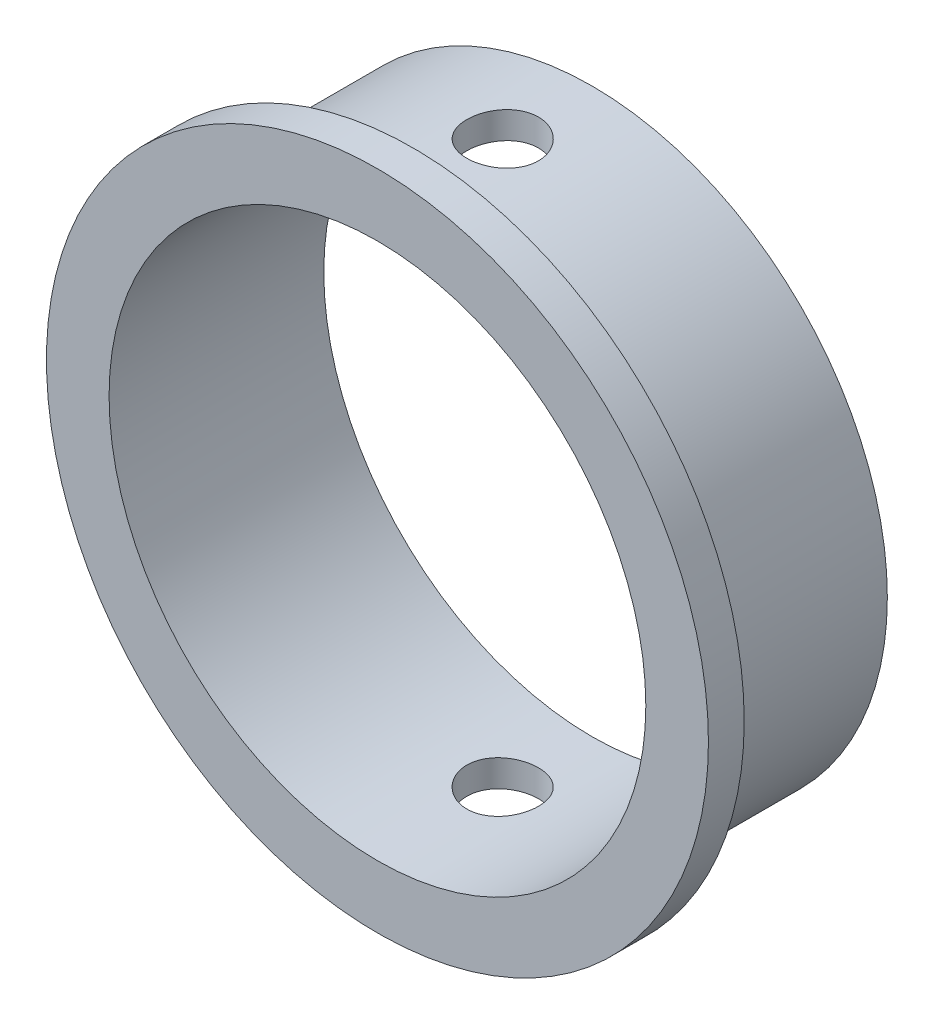
SolidWorks part; units mm, degrees
ref_plane "Alzado" through (0, 0, 0) normal (0, 0, 1) x (1, 0, 0)
ref_plane "Planta" through (0, 0, 0) normal (0, 1, 0) x (1, 0, 0)
ref_plane "Vista lateral" through (0, 0, 0) normal (1, 0, 0) x (0, 0, -1)
sketch "Croquis2" plane through (0, 0, 0) normal (0, 0, 1) x (1, 0, 0)
  circle A0 centre (0, 0) radius 16.5
  circle A1 centre (0, 0) radius 15
  dimension "D1" = 33
  dimension "D2" = 30
extrude "Saliente-Extruir1" add sketch "Croquis2" along normal blind 12
sketch "Croquis3" plane through (0, 0, 12) normal (0, 0, 1) x (1, 0, 0)
  circle A0 centre (0, 0) radius 15
  circle A1 centre (0, 0) radius 18.5
  circle A2 centre (0, 0) radius 16.5 construction
  dimension "D1" = 2
extrude "Saliente-Extruir2" add sketch "Croquis3" against normal blind 2 contours A1
sketch "Croquis4" plane through (0, 0, 10) normal (0, 0, -1) x (-1, 0, 0)
  circle A0 centre (0, 0) radius 15
extrude "Cortar-Extruir1" cut sketch "Croquis4" against normal blind 2
sketch "Croquis5" plane through (0, 0, 0) normal (0, 1, 0) x (1, 0, 0)
  line L0 (-16.5, -5) -> (16.5, -5) construction
  line L1 (-16.5, 0) -> (-16.5, -10) construction
  line L2 (16.5, -10) -> (16.5, 0) construction
  line L3 (0, 0) -> (0, -10) construction
  line L4 (18.5, -10) -> (-18.5, -10) construction
  circle A0 centre (0, -5) radius 2
  dimension "D1" = 4
extrude "Cortar-Extruir2" cut sketch "Croquis5" against normal blind 21 and the other way blind 22
